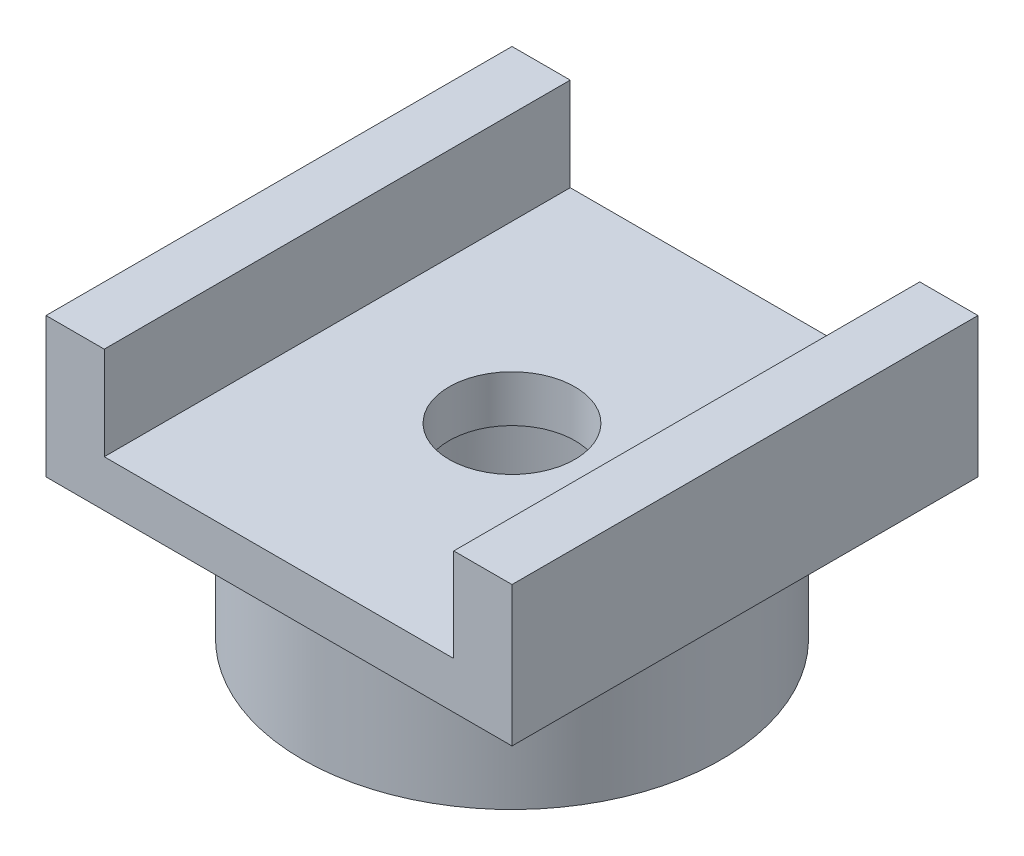
SolidWorks part; units mm, degrees
material "PE haute densité"
ref_plane "Plan de face" through (0, 0, 0) normal (0, 0, 1) x (1, 0, 0)
ref_plane "Plan de dessus" through (0, 0, 0) normal (0, 1, 0) x (1, 0, 0)
ref_plane "Plan de droite" through (0, 0, 0) normal (1, 0, 0) x (0, 0, -1)
sketch "Esquisse1" plane through (0, 0, 0) normal (0, 1, 0) x (1, 0, 0)
  circle A0 centre (0, 0) radius 4.5
  circle A1 centre (0, 0) radius 2.75
  dimension "D1" = 5.5
  dimension "D2" = 9
extrude "Boss.-Extru.1" add sketch "Esquisse1" against normal blind 3
sketch "Esquisse3" plane through (0, 0, 0) normal (0, 1, 0) x (1, 0, 0)
  line L1 (-5, -5) -> (5, -5)
  line L2 (-5, -5) -> (-5, 5)
  line L3 (-5, 5) -> (5, 5)
  line L4 (5, -5) -> (5, 5)
  line L5 (-5, -5) -> (5, 5) construction
  line L6 (-5, 5) -> (5, -5) construction
  circle A0 centre (0, 0) radius 1.35
  point P0 (0, 0)
  dimension "D1" = 2.7
  dimension "D2" = 10
extrude "Boss.-Extru.2" add sketch "Esquisse3" along normal blind 1
sketch "Esquisse4" plane through (0, 1, 0) normal (0, 1, 0) x (1, 0, 0)
  line L0 (-5, -5) -> (5, -5) construction
  line L1 (-5, 5) -> (-3.75, 5)
  line L2 (-5, 5) -> (-5, -5)
  line L3 (-5, -5) -> (-3.75, -5)
  line L4 (-3.75, 5) -> (-3.75, -5)
  line L5 (5, 5) -> (-5, 5) construction
  line L6 (5, -5) -> (3.75, -5)
  line L7 (5, -5) -> (5, 5)
  line L8 (5, 5) -> (3.75, 5)
  line L9 (3.75, -5) -> (3.75, 5)
  dimension "D1" = 7.5
extrude "Boss.-Extru.3" add sketch "Esquisse4" along normal blind 2
